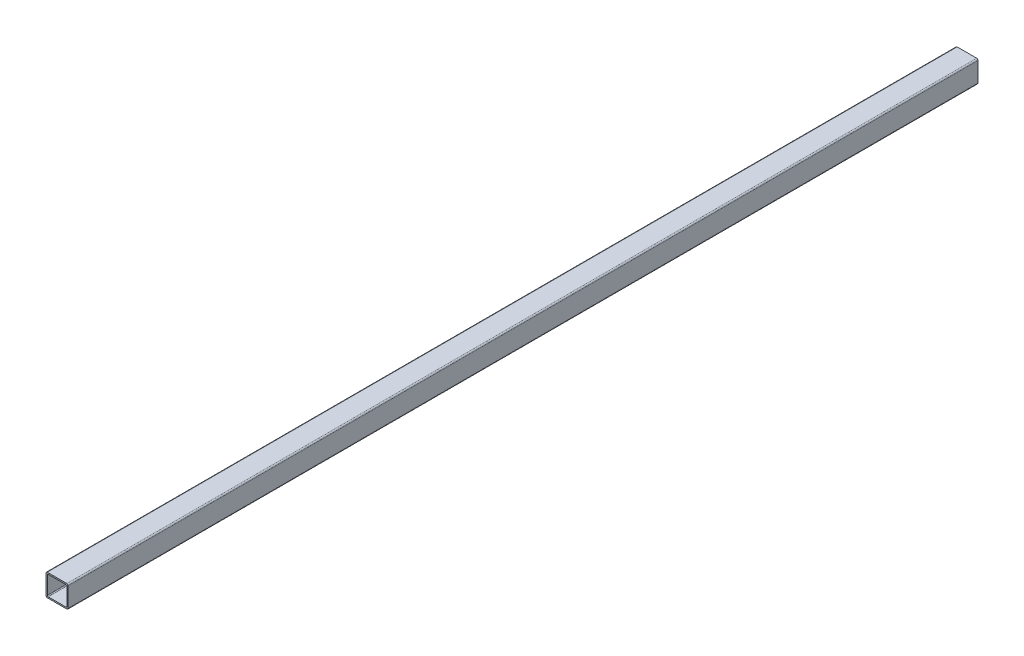
SolidWorks part; units mm, degrees
material "AISI 1020"
ref_plane "Спереди" through (0, 0, 0) normal (0, 0, 1) x (1, 0, 0)
ref_plane "Сверху" through (0, 0, 0) normal (0, 1, 0) x (1, 0, 0)
ref_plane "Справа" through (0, 0, 0) normal (1, 0, 0) x (0, 0, -1)
sketch "Эскиз1" plane through (0, 0, 0) normal (0, 0, 1) x (1, 0, 0)
  line B0 (-22, 25) -> (22, 25)
  line B1 (-25, 22) -> (-25, -22)
  line B2 (-22, -25) -> (22, -25)
  line B3 (25, 22) -> (25, -22)
  line B4 (-20, 22) -> (20, 22)
  line B5 (-22, 20) -> (-22, -20)
  line B6 (-20, -22) -> (20, -22)
  line B7 (22, 20) -> (22, -20)
  arc B8 (-25, -22) -> (-22, -25) centre (-22, -22) ccw
  arc B9 (22, -25) -> (25, -22) centre (22, -22) ccw
  arc B10 (22, 25) -> (25, 22) centre (22, 22) cw
  arc B11 (-22, 25) -> (-25, 22) centre (-22, 22) ccw
  arc B12 (-22, -20) -> (-20, -22) centre (-20, -20) ccw
  arc B13 (20, -22) -> (22, -20) centre (20, -20) ccw
  arc B14 (20, 22) -> (22, 20) centre (20, 20) cw
  arc B15 (-20, 22) -> (-22, 20) centre (-20, 20) ccw
sketch_block_instance "Труба профильная 50х50х3-1"
sketch_block "Труба профильная 50х50х3" parameters "D3"=3, "D4"=2, "D1"=50, "D2"=3
extrude "Бобышка-Вытянуть1" add sketch "Эскиз1" against normal up to vertex (2054.3307 mm away)
